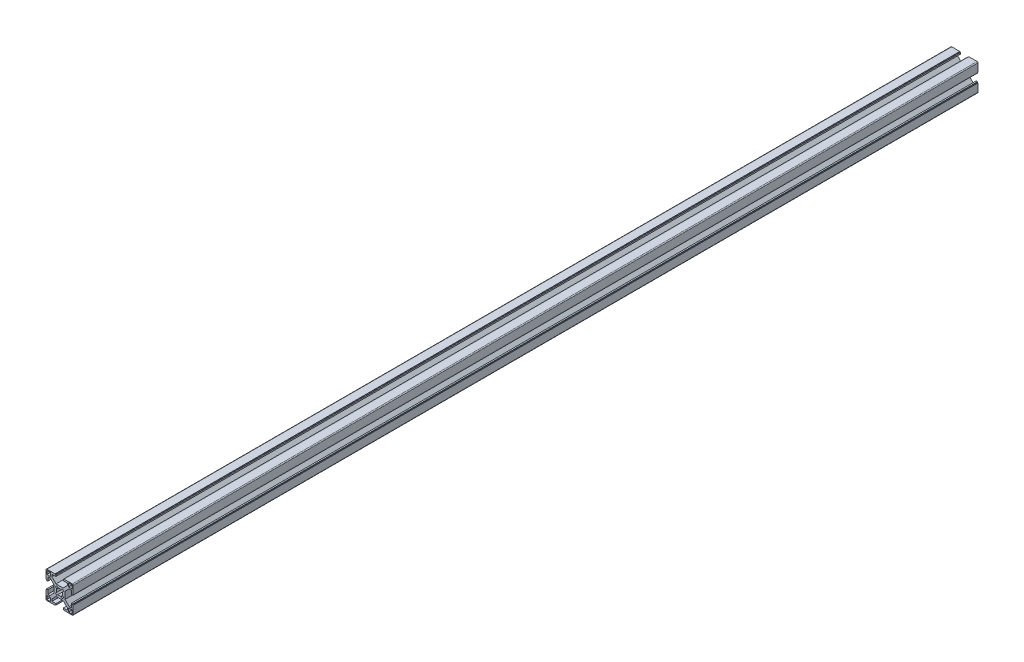
SolidWorks part; units mm, degrees
material "6063-O"
ref_plane "Plano frontal" through (0, 0, 0) normal (0, 0, 1) x (1, 0, 0)
ref_plane "Plano superior" through (0, 0, 0) normal (0, 1, 0) x (1, 0, 0)
ref_plane "Plano direito" through (0, 0, 0) normal (1, 0, 0) x (0, 0, -1)
sketch "Esboço1" plane through (0, 0, 0) normal (0, 0, 1) x (1, 0, 0)
  line L5 (0, 0) -> (-17.7944, 17.7944) construction
  line L6 (0, 3.5) -> (0, 6)
  line L8 (0, 6) -> (-3.8787, 6)
  line L9 (-3.5, 0) -> (-6, 0)
  line L48 (-6, 0) -> (-6, 3.8787)
  line L49 (-3.8787, 6) -> (-8.5, 10.6213)
  line L50 (-6, 3.8787) -> (-10.6213, 8.5)
  line L51 (0, 0) -> (-12.921, 0) construction
  line L52 (-8.5, 13) -> (-4.1, 13)
  line L53 (-4.1, 13) -> (-4.1, 14.5)
  line L54 (-4.1, 14.5) -> (-5.1, 14.5)
  line L55 (-5.1, 14.5) -> (-5.1, 15)
  line L56 (-5.1, 15) -> (-15, 15)
  line L57 (-15, 5.1) -> (-15, 15)
  line L58 (-14.5, 5.1) -> (-15, 5.1)
  line L59 (-14.5, 4.1) -> (-14.5, 5.1)
  line L60 (-13, 4.1) -> (-14.5, 4.1)
  line L61 (-13, 8.5) -> (-13, 4.1)
  line L62 (-1.6646, 3.0788) -> (-3.182, 4.5962)
  line L63 (-3.0788, 1.6646) -> (-4.5962, 3.182)
  line L64 (-4.5962, 3.182) -> (-3.182, 4.5962)
  line L65 (-8.5, 13) -> (-8.5, 10.6213)
  line L66 (-10, 14) -> (-14, 14)
  line L67 (-10, 14) -> (-10, 10)
  line L68 (-10, 10) -> (-14, 10)
  line L69 (-14, 14) -> (-14, 10)
  line L70 (-10, 14) -> (-14, 10) construction
  line L71 (-10, 10) -> (-14, 14) construction
  line L72 (-13, 8.5) -> (-10.6213, 8.5)
  circle A1 centre (0, 0) radius 3.5
  point P25 (-12, 12)
  dimension "D5" = 10.9
  dimension "D9" = 5.5
  dimension "D10" = 2
  dimension "D11" = 4
  dimension "D12" = 4
  dimension "D13" = 1
  dimension "D1" = 7
  dimension "D2" = 6
  dimension "D3" = 3
  dimension "D4" = 9.9
  dimension "D6" = 0.5
  dimension "D7" = 1.5
  dimension "D8" = 15
  dimension "D14" = 6.5
extrude "Ressalto-extrusão1" add sketch "Esboço1" along normal blind 1000 contours A1 L6 L8 L49 L65 L52 L53 L54 L55 L56 L57 L58 L59 L60 L61 L72 L50 L48 L9 L63 L64 L62 L69 L66 L67 L68
sketch "Esboço3" plane through (0, 0, 0) normal (1, 0, 0) x (0, 0, -1)
  line L0 (0, 0) -> (-1000, 0) construction
  dimension "D1" = 1000
pattern_circular "PadrãoCircular1" count 4 every 90 about axis through (0, 0, 0) along (0, 0, 1) of "Ressalto-extrusão1"
fillet "Filete1" radius 1 4 edges at (15, 15, 500) (-15, 15, 500) (-15, -15, 500) (15, -15, 500)
